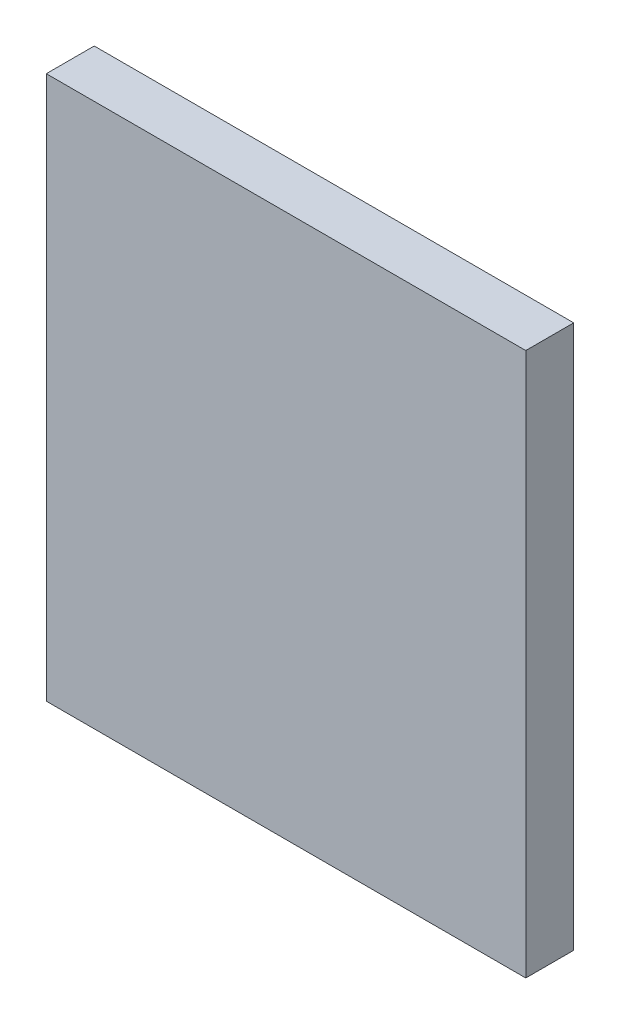
SolidWorks part; units mm, degrees
ref_plane "Front Plane" through (0, 0, 0) normal (0, 0, 1) x (1, 0, 0)
ref_plane "Top Plane" through (0, 0, 0) normal (0, 1, 0) x (1, 0, 0)
ref_plane "Right Plane" through (0, 0, 0) normal (1, 0, 0) x (0, 0, -1)
sketch "Sketch1" plane through (0, 0, 0) normal (0, 0, 1) x (1, 0, 0)
  line L1 (-30, -34) -> (30, -34)
  line L2 (-30, -34) -> (-30, 34)
  line L3 (-30, 34) -> (30, 34)
  line L4 (30, -34) -> (30, 34)
  line L5 (-30, -34) -> (30, 34) construction
  line L6 (-30, 34) -> (30, -34) construction
  point P0 (0, 0)
  dimension "D1" = 60
  dimension "D2" = 68
extrude "Boss-Extrude1" add sketch "Sketch1" along normal blind 6
